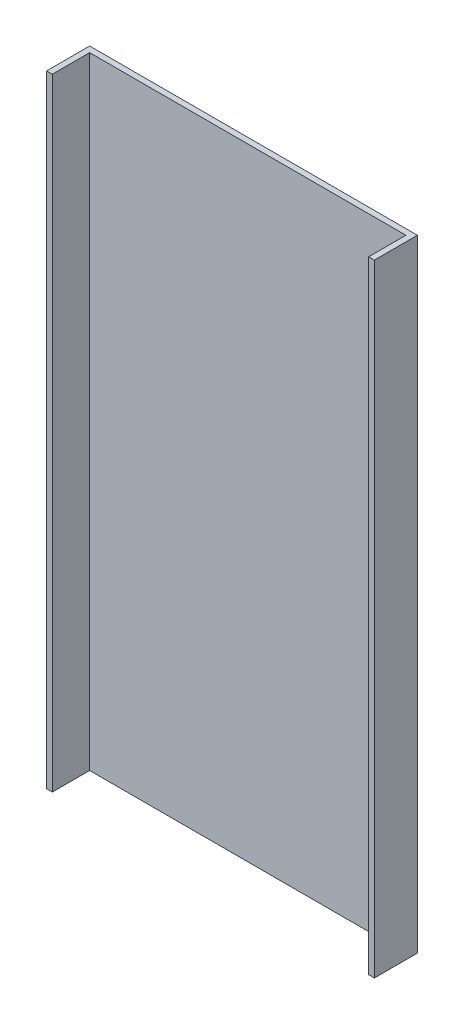
SolidWorks part; units mm, degrees
ref_plane "Front Plane" through (0, 0, 0) normal (0, 0, 1) x (1, 0, 0)
ref_plane "Top Plane" through (0, 0, 0) normal (0, 1, 0) x (1, 0, 0)
ref_plane "Right Plane" through (0, 0, 0) normal (1, 0, 0) x (0, 0, -1)
sketch "Sketch1" plane through (0, 0, 0) normal (0, 0, 1) x (1, 0, 0)
  line L1 (0, 0) -> (72.46, 0)
  line L2 (0, 0) -> (0, 137.44)
  line L3 (0, 137.44) -> (72.46, 137.44)
  line L4 (72.46, 0) -> (72.46, 137.44)
  dimension "D1" = 72.46
  dimension "D2" = 137.44
extrude "Boss-Extrude1" add sketch "Sketch1" along normal blind 1.27
sketch "Sketch2" plane through (0, 0, 1.27) normal (0, 0, 1) x (1, 0, 0)
  line L0 (0, 0) -> (72.46, 0) construction
  line L1 (0, 137.44) -> (1.27, 137.44)
  line L2 (0, 137.44) -> (0, 0)
  line L3 (0, 0) -> (1.27, 0)
  line L4 (1.27, 137.44) -> (1.27, 0)
  line L5 (72.46, 137.44) -> (0, 137.44) construction
  line L6 (72.46, 0) -> (71.19, 0)
  line L7 (72.46, 0) -> (72.46, 137.44)
  line L8 (72.46, 137.44) -> (71.19, 137.44)
  line L9 (71.19, 0) -> (71.19, 137.44)
  dimension "D1" = 1.27
  dimension "D2" = 1.27
extrude "Boss-Extrude2" add sketch "Sketch2" along normal blind 8.25
